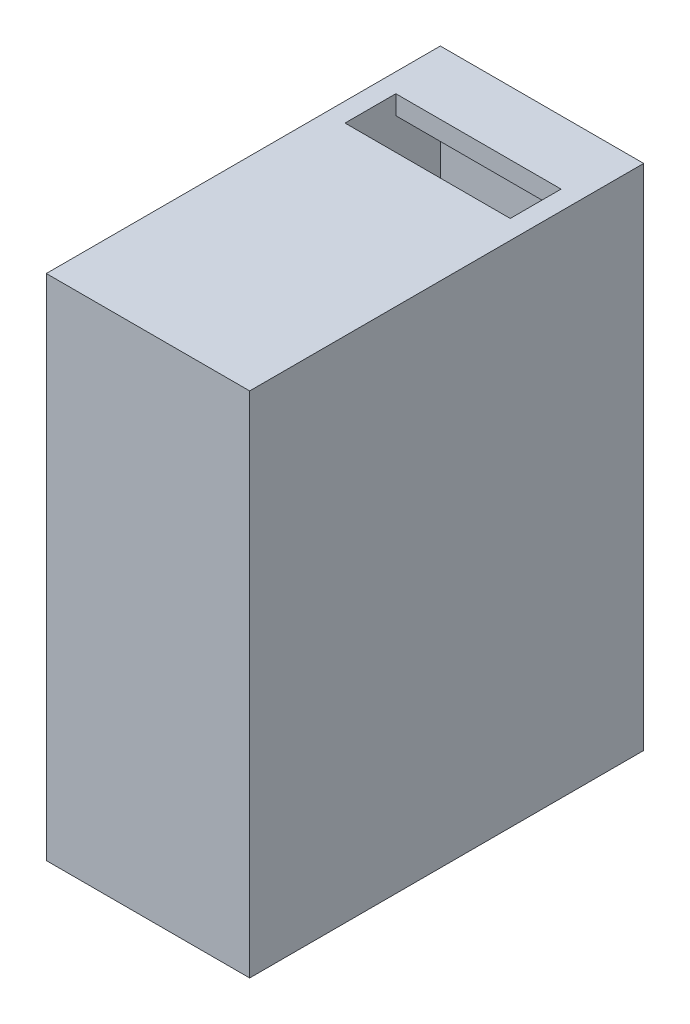
SolidWorks part; units mm, degrees
ref_plane "Front Plane" through (0, 0, 0) normal (0, 0, 1) x (1, 0, 0)
ref_plane "Top Plane" through (0, 0, 0) normal (0, 1, 0) x (1, 0, 0)
ref_plane "Right Plane" through (0, 0, 0) normal (1, 0, 0) x (0, 0, -1)
sketch "Sketch1" plane through (0, 0, 0) normal (0, 1, 0) x (1, 0, 0)
  line L1 (0, 0) -> (16, 0)
  line L2 (0, 0) -> (0, -31)
  line L3 (0, -31) -> (16, -31)
  line L4 (16, 0) -> (16, -31)
  dimension "D1" = 16
  dimension "D2" = 31
extrude "Boss-Extrude1" add sketch "Sketch1" along normal blind 40
shell "Shell1" thickness 1.5
sketch "Sketch2" plane through (0, 40, 0) normal (0, 1, 0) x (1, 0, 0)
  line L0 (16, 0) -> (0, 0) construction
  line L1 (1.5, -5) -> (14.5, -5)
  line L2 (1.5, -5) -> (1.5, -9)
  line L3 (1.5, -9) -> (14.5, -9)
  line L4 (14.5, -5) -> (14.5, -9)
  line L5 (16, -31) -> (16, 0) construction
  dimension "D1" = 13
  dimension "D2" = 5
  dimension "D3" = 4
  dimension "D4" = 1.5
extrude "Cut-Extrude1" cut sketch "Sketch2" against normal up to vertex (1.5 mm away)
sketch "Sketch3" plane through (0, 0, 0) normal (0, 0, -1) x (-1, 0, 0)
  line L0 (-16, 0) -> (0, 0) construction
  line L1 (-14.7811, 20) -> (-1.2811, 20)
  line L2 (-14.7811, 20) -> (-14.7811, -1)
  line L3 (-14.7811, -1) -> (-1.2811, -1)
  line L4 (-1.2811, 20) -> (-1.2811, -1)
  dimension "D1" = 13.5
  dimension "D2" = 1
  dimension "D3" = 21
extrude "Cut-Extrude2" cut sketch "Sketch3" against normal up to vertex (1.5 mm away)
